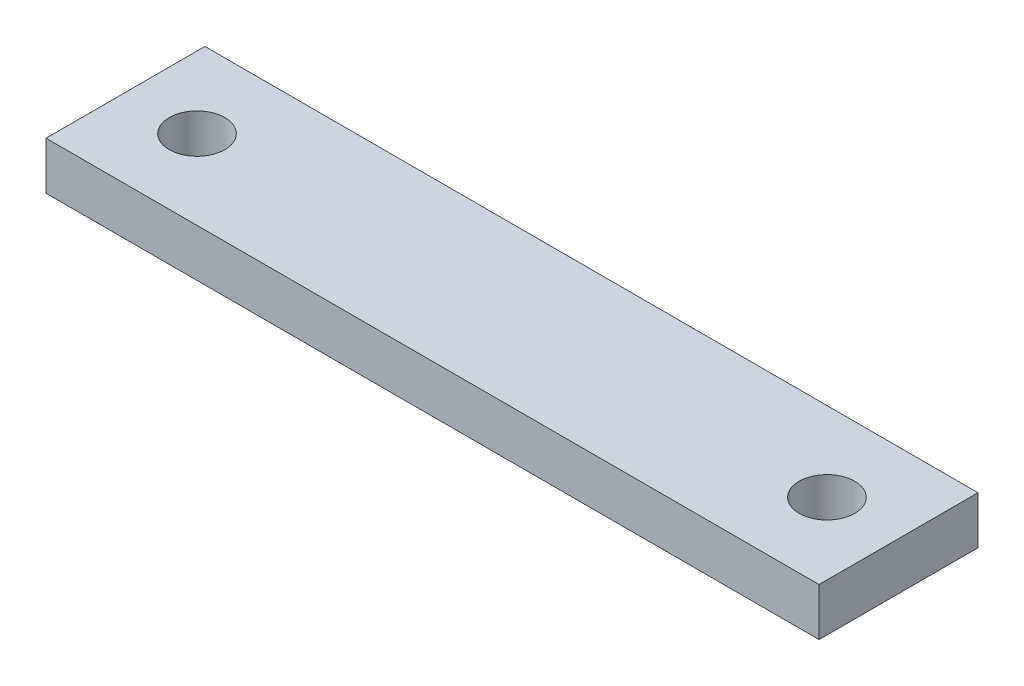
SolidWorks part; units mm, degrees
ref_plane "Front Plane" through (0, 0, 0) normal (0, 0, 1) x (1, 0, 0)
ref_plane "Top Plane" through (0, 0, 0) normal (0, 1, 0) x (1, 0, 0)
ref_plane "Right Plane" through (0, 0, 0) normal (1, 0, 0) x (0, 0, -1)
sketch "Sketch1" plane through (0, 0, 0) normal (0, 1, 0) x (1, 0, 0)
  line L1 (-24.315, 5) -> (24.315, 5)
  line L2 (-24.315, 5) -> (-24.315, -5)
  line L3 (-24.315, -5) -> (24.315, -5)
  line L4 (24.315, 5) -> (24.315, -5)
  point P4 (0, -5)
  point P6 (-24.315, 0)
  dimension "D1" = 48.63
  dimension "D2" = 10
extrude "Boss-Extrude1" add sketch "Sketch1" along normal blind 3
sketch "Sketch2" plane through (0, 3, 0) normal (0, 1, 0) x (1, 0, 0)
  circle A0 centre (-19.815, 0) radius 1.75
  circle A1 centre (19.8135, 0) radius 1.75
  dimension "D1" = 39.6285
  dimension "D2" = 19.815
extrude "Cut-Extrude1" cut sketch "Sketch2" against normal through all
